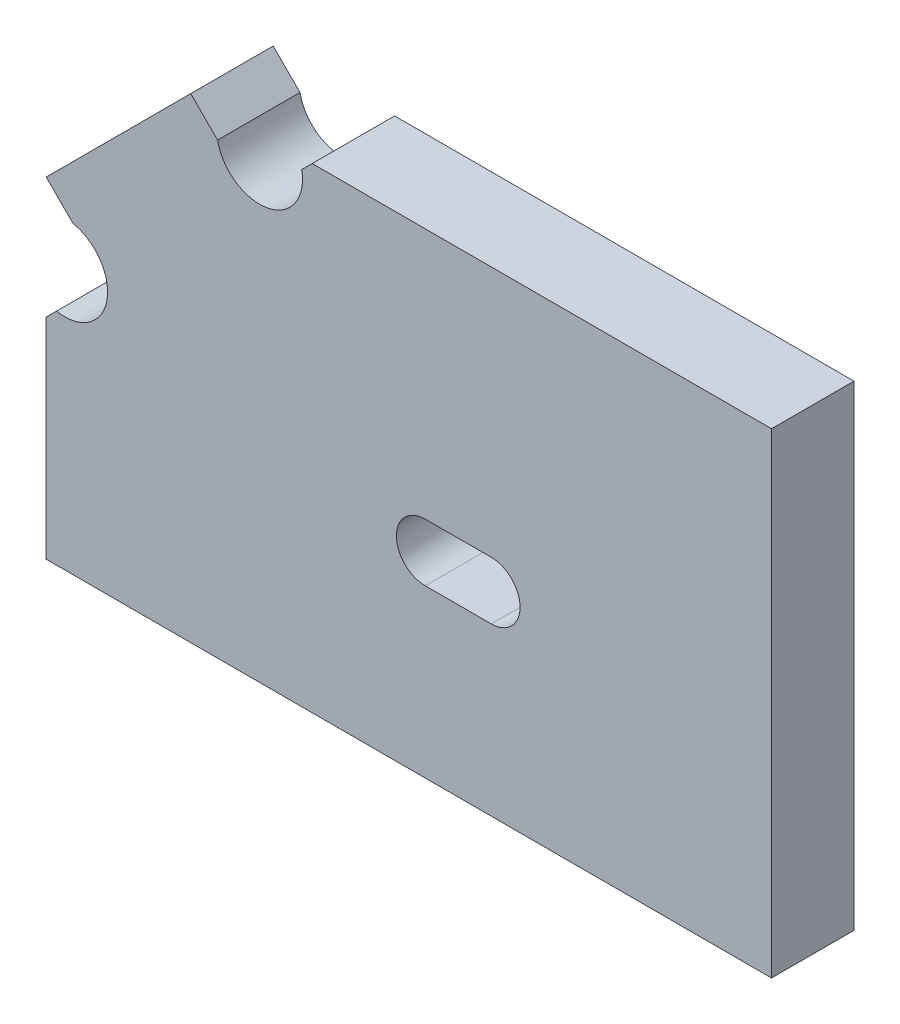
SolidWorks part; units mm, degrees
ref_plane "Front Plane" through (0, 0, 0) normal (0, 0, 1) x (1, 0, 0)
ref_plane "Top Plane" through (0, 0, 0) normal (0, 1, 0) x (1, 0, 0)
ref_plane "Right Plane" through (0, 0, 0) normal (1, 0, 0) x (0, 0, -1)
sketch "Sketch1" plane through (0, 0, 0) normal (0, 0, 1) x (1, 0, 0)
  line L1 (-0.8301, 34.3742) -> (69.9342, 34.3742)
  line L3 (-41.8258, -38.9048) -> (69.9342, -38.9048)
  line L4 (69.9342, 34.3742) -> (69.9342, -38.9048)
  line L5 (-0.8301, 34.3742) -> (-2.4403, 32.7641)
  line L6 (-19.5319, 34.3513) -> (-15.401, 30.2204)
  line L7 (-41.803, 12.0803) -> (-37.672, 7.9494)
  line L8 (-40.2157, -5.0114) -> (-41.8258, -6.6215)
  line L9 (62.6952, 27.1352) -> (81.7452, 46.1852) construction
  line L10 (70.3152, 34.7552) -> (-32.4864, 34.7552) construction
  line L11 (-37.672, 7.9494) -> (-15.401, 30.2204) construction
  line L12 (70.3152, -30.0148) -> (-19.8548, -30.0148) construction
  line L13 (-37.672, 7.9494) -> (-32.4635, 2.7408) construction
  line L15 (-19.5319, 34.3513) -> (-41.803, 12.0803)
  line L16 (-32.4635, 2.7408) -> (-40.2157, -5.0114) construction
  line L17 (-41.8258, -6.6215) -> (-41.8258, -38.9048)
  line L18 (-2.4403, 32.7641) -> (-10.1925, 25.0119) construction
  line L19 (-10.1925, 25.0119) -> (-15.401, 30.2204) construction
  arc A0 (-15.401, 30.2204) -> (-2.4403, 32.7641) centre (-8.9206, 31.4922) ccw
  arc A1 (-37.672, 7.9494) -> (-40.2157, -5.0114) centre (-38.9439, 1.469) cw
  dimension "D4" = 111.76
  dimension "D5" = 6.604
  dimension "D1" = 0.381
  dimension "D2" = 31.496
  dimension "D3" = 8.89
  dimension "D6" = 135
  dimension "D7" = 135
  dimension "D8" = 115.062
  dimension "D9" = 13.208
  dimension "D10" = 5.842
extrude "Boss-Extrude1" add sketch "Sketch1" along normal blind 12.7
sketch "Sketch2" plane through (0, 0, 0) normal (0, 0, -1) x (-1, 0, 0)
  line L0 (-26.7542, -8.8058) -> (-16.5942, -8.8058) construction
  line L1 (-26.7542, -4.3608) -> (-16.5942, -4.3608)
  line L2 (-26.7542, -13.2508) -> (-16.5942, -13.2508)
  line L6 (0.8301, 34.3742) -> (-69.9342, 34.3742) construction
  line L7 (-69.9342, 34.3742) -> (-69.9342, -38.9048) construction
  arc A0 (-26.7542, -4.3608) -> (-26.7542, -13.2508) centre (-26.7542, -8.8058) ccw
  arc A1 (-16.5942, -13.2508) -> (-16.5942, -4.3608) centre (-16.5942, -8.8058) ccw
  point P2 (-21.6742, -8.8058)
  dimension "D1" = 10.16
  dimension "D2" = 8.89
  dimension "D3" = 43.18
  dimension "D4" = 43.18
extrude "Cut-Extrude1" cut sketch "Sketch2" against normal through all
